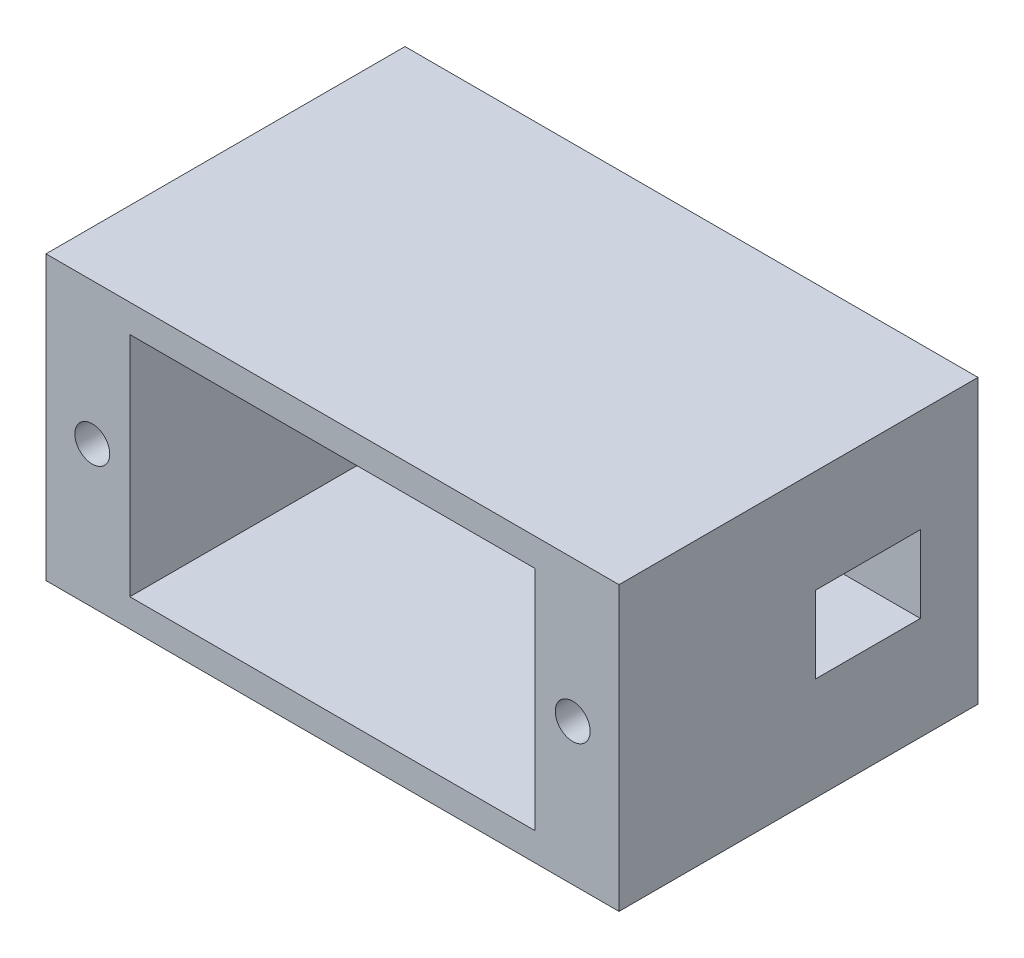
SolidWorks part; units mm, degrees
material "ABS"
ref_plane "Front Plane" through (0, 0, 0) normal (0, 0, 1) x (1, 0, 0)
ref_plane "Top Plane" through (0, 0, 0) normal (0, 1, 0) x (1, 0, 0)
ref_plane "Right Plane" through (0, 0, 0) normal (1, 0, 0) x (0, 0, -1)
sketch "Sketch1" plane through (0, 0, 0) normal (0, 0, 1) x (1, 0, 0)
  line L1 (-16.4, -8.1) -> (16.4, -8.1)
  line L2 (-16.4, -8.1) -> (-16.4, 8.1)
  line L3 (-16.4, 8.1) -> (16.4, 8.1)
  line L4 (16.4, -8.1) -> (16.4, 8.1)
extrude "Boss-Extrude1" add sketch "Sketch1" along normal mid plane 20.55 from offset 5.125
sketch "Sketch2" plane through (0, 0, 0) normal (0, 0, 1) x (1, 0, 0)
  line L1 (-11.6, -6.5) -> (11.6, -6.5)
  line L2 (-11.6, -6.5) -> (-11.6, 6.5)
  line L3 (-11.6, 6.5) -> (11.6, 6.5)
  line L4 (11.6, -6.5) -> (11.6, 6.5)
extrude "Cut-Extrude1" cut sketch "Sketch2" against normal mid plane 17.25 from offset 3.475
sketch "Sketch3" plane through (0, 0, 0) normal (0, 0, 1) x (1, 0, 0)
  circle A0 centre (-13.75, 0) radius 1
extrude "Cut-Extrude2" cut sketch "Sketch3" against normal mid plane 6 from offset 2.15
sketch "Sketch4" plane through (0, 0, 0) normal (0, 0, 1) x (1, 0, 0)
  circle A0 centre (13.75, 0) radius 1
extrude "Cut-Extrude3" cut sketch "Sketch4" against normal mid plane 6 from offset 2.15
sketch "Sketch5" plane through (0, 0, 0) normal (0, 0, 1) x (1, 0, 0)
  circle A0 centre (5.5, 0) radius 3.15
extrude "Cut-Extrude4" cut sketch "Sketch5" against normal mid plane 2.6 from offset 14.1
sketch "Sketch6" plane through (0, 0, 0) normal (1, 0, 0) x (0, 0, -1)
  line L1 (6.1, -2.2) -> (12.1, -2.2)
  line L2 (6.1, -2.2) -> (6.1, 2.2)
  line L3 (6.1, 2.2) -> (12.1, 2.2)
  line L4 (12.1, -2.2) -> (12.1, 2.2)
extrude "Cut-Extrude5" cut sketch "Sketch6" against normal mid plane 4.8 from offset 14
